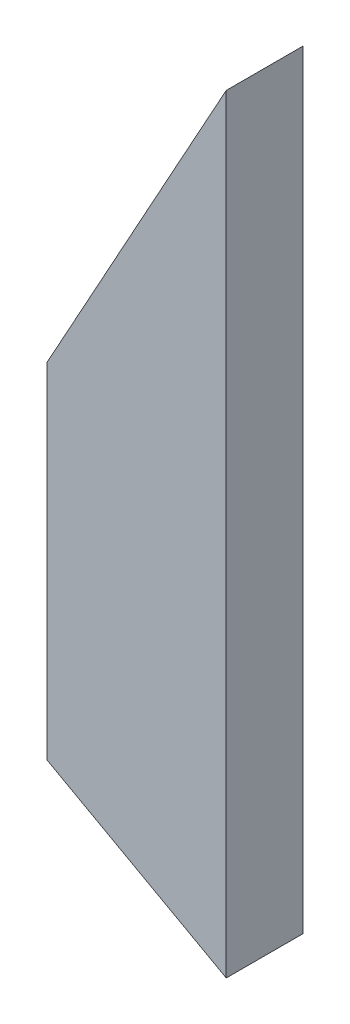
SolidWorks part; units mm, degrees
material "Balsa"
ref_plane "Front Plane" through (0, 0, 0) normal (0, 0, 1) x (1, 0, 0)
ref_plane "Top Plane" through (0, 0, 0) normal (0, 1, 0) x (1, 0, 0)
ref_plane "Right Plane" through (0, 0, 0) normal (1, 0, 0) x (0, 0, -1)
sketch "Sketch1" plane through (0, 0, 0) normal (0, 0, 1) x (1, 0, 0)
  line L0 (44.45, 190.5) -> (-44.45, 29.23)
  line L1 (-44.45, 190.5) -> (44.45, 190.5)
  line L2 (-44.45, 190.5) -> (-44.45, -190.5)
  line L3 (-44.45, -190.5) -> (44.45, -190.5)
  line L4 (44.45, 190.5) -> (44.45, -190.5)
  line L5 (-44.45, 190.5) -> (44.45, -190.5) construction
  line L6 (-44.45, -190.5) -> (44.45, 190.5) construction
  line L7 (44.45, -190.5) -> (-44.45, -141.3131)
  point P0 (0, 0)
  dimension "D1" = 381
  dimension "D2" = 88.9
  dimension "D3" = 184.15
  dimension "D4" = 101.6
extrude "Boss-Extrude1" add sketch "Sketch1" along normal blind 38.1
